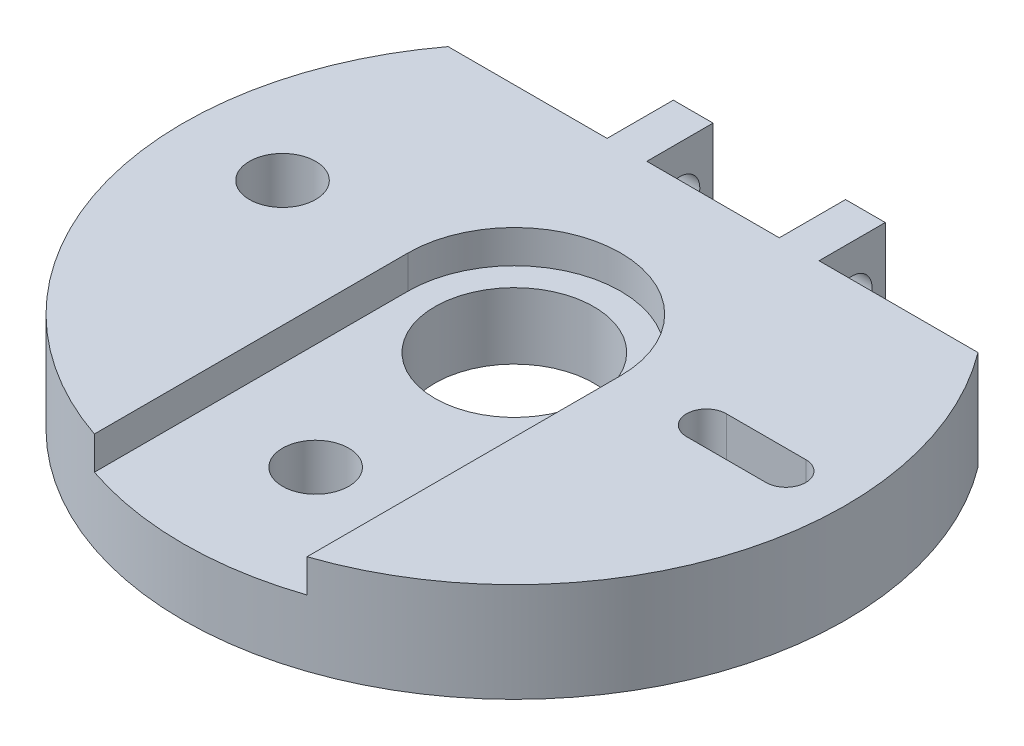
SolidWorks part; units mm, degrees
ref_plane "Piano frontale" through (0, 0, 0) normal (0, 0, 1) x (1, 0, 0)
ref_plane "Piano superiore" through (0, 0, 0) normal (0, 1, 0) x (1, 0, 0)
ref_plane "Piano destro" through (0, 0, 0) normal (1, 0, 0) x (0, 0, -1)
sketch "Schizzo1" plane through (0, 0, 0) normal (0, 1, 0) x (1, 0, 0)
  line L0 (0, 74.1119) -> (0, -71.8566) construction
  line L1 (-67.4732, 0) -> (99.4909, 0) construction
  line L2 (-40, 30) -> (-16, 30)
  line L3 (-16, 30) -> (-16, 40)
  line L4 (-16, 40) -> (-10, 40)
  line L5 (-10, 40) -> (-10, 30)
  line L6 (-10, 30) -> (10, 30)
  line L7 (10, 40) -> (10, 30)
  line L8 (16, 40) -> (10, 40)
  line L9 (16, 30) -> (16, 40)
  line L10 (40, 30) -> (16, 30)
  line L15 (29, 0) -> (41, 0) construction
  line L16 (29, 3) -> (41, 3)
  line L17 (29, -3) -> (41, -3)
  arc A0 (-40, 30) -> (40, 30) centre (0, 0) ccw
  circle A1 centre (0, 0) radius 12
  circle A2 centre (0, -30) radius 5
  arc A6 (29, 3) -> (29, -3) centre (29, 0) ccw
  arc A7 (41, -3) -> (41, 3) centre (41, 0) ccw
  point P14 (0, 30)
  point P26 (35, 0)
  dimension "D1" = 100
  dimension "D2" = 24
  dimension "D9" = 10
  dimension "D3" = 10
  dimension "D4" = 10
  dimension "D5" = 32
  dimension "D6" = 20
  dimension "D7" = 30
  dimension "D8" = 30
  dimension "D11" = 12
  dimension "D12" = 29
  dimension "D13" = 6
extrude "Estrusione-Estrusione1" add sketch "Schizzo1" along normal mid plane 15
sketch "Schizzo3" plane through (0, 7.5, 0) normal (0, 1, 0) x (1, 0, 0)
  line L0 (-29.8218, 0) -> (21.8888, 0) construction
  line L1 (-16.05, 0) -> (-16.05, -47.354)
  line L2 (16.05, 0) -> (16.05, -47.354)
  arc A0 (16.05, 0) -> (-16.05, 0) centre (0, 0) ccw
  arc A1 (-40, 30) -> (40, 30) centre (0, 0) ccw construction
  circle M6 centre (0, -30) radius 5
  circle M7 centre (0, 0) radius 12
  arc M9 (-40, 30) -> (40, 30) centre (0, 0) ccw
  dimension "D1" = 32.1
extrude "Taglio-Estrusione1" cut sketch "Schizzo3" against normal blind 5 and the other way through all contours L0 L1 L2 M9 M7 M6 | A0 L0 M7
sketch "Schizzo4" plane through (0, 7.5, 0) normal (0, 1, 0) x (1, 0, 0)
  line L0 (-48.5728, 0) -> (21.5879, 0) construction
  circle A0 centre (-35, 0) radius 5
  dimension "D2" = 10
  dimension "D1" = 35
extrude "Taglio-Estrusione2" cut sketch "Schizzo4" against normal blind 10
hole_wizard "Foro Ø7.0 (7)-1" positions "Schizzo5" profile "Schizzo6" hole size "Ø7.0" standard "ISO" end condition up to next
sketch "Schizzo5" plane through (0, -2.5, 0) normal (0, 1, 0) x (1, 0, 0)
  point P0 (-35, 0)
sketch "Schizzo6" plane through (-35, -2.5, 0) normal (1, 0, 0) x (0, 0, 1)
  line L0 (0, 0) -> (0, 5)
  line L1 (0, 5) -> (3.5, 5)
  line L2 (3.5, 5) -> (3.5, 0)
  line L5 (3.5, 0) -> (0, 0)
  line L11 (0, -6.35) -> (0, 107.95) construction
  dimension "Thru Hole Dia." = 7
  dimension "Thru Hole Depth" = 5
hole_wizard "Foro Ø6.0 (6)-1" positions "Schizzo9" profile "Schizzo8" hole size "Ø6.0" standard "ISO" end condition through all
sketch "Schizzo9" plane through (-16, 0, 0) normal (-1, 0, 0) x (0, 0, 1)
  line L0 (0, 0) -> (-49.3121, 0) construction
  line L1 (-30, 7.5) -> (-40, 7.5) construction
  line L2 (-30, 7.5) -> (-30, -7.5) construction
  point P6 (-35, 0)
  dimension "D1" = 7.5
  dimension "D2" = 5
sketch "Schizzo8" plane through (-16, 0, -35) normal (0, 1, 0) x (0, 0, 1)
  line L0 (0, 0) -> (0, 66)
  line L1 (0, 66) -> (3, 66)
  line L2 (3, 66) -> (3, 0)
  line L5 (3, 0) -> (0, 0)
  line L11 (0, -6.35) -> (0, 107.95) construction
  dimension "Thru Hole Dia." = 6
  dimension "Thru Hole Depth" = 66
sketch "Schizzo11" plane through (0, -7.5, 0) normal (0, -1, 0) x (1, 0, 0)
  line L0 (0, 0) -> (0, 50)
  arc A0 (40, -30) -> (-40, -30) centre (0, 0) ccw construction
